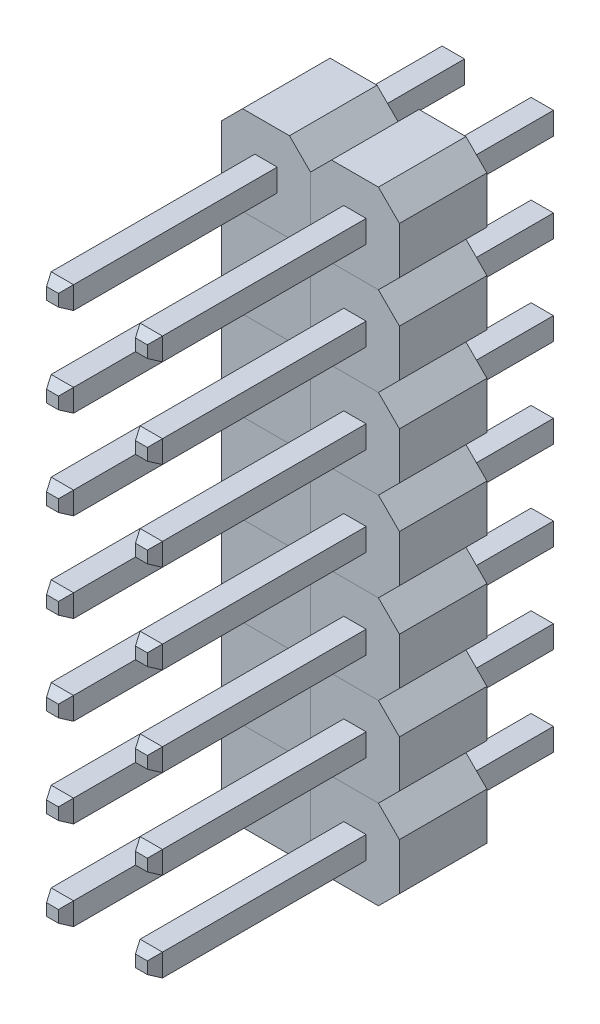
SolidWorks part; units mm, degrees
ref_plane "Спереди" through (0, 0, 0) normal (0, 0, 1) x (1, 0, 0)
ref_plane "Сверху" through (0, 0, 0) normal (0, 1, 0) x (1, 0, 0)
ref_plane "Справа" through (0, 0, 0) normal (1, 0, 0) x (0, 0, -1)
sketch "Эскиз1" plane through (0, 0, 0) normal (0, 0, 1) x (1, 0, 0)
  line L1 (-2.54, -8.89) -> (0, -8.89)
  line L2 (-2.54, -8.89) -> (-2.54, -6.35)
  line L3 (-2.54, -6.35) -> (0, -6.35)
  line L4 (0, -8.89) -> (0, -6.35)
  line L5 (0, -55) -> (0, 55) construction
  line L6 (-2.54, -8.89) -> (0, -6.35) construction
  point P6 (-1.27, -7.62)
  dimension "D1" = 2.54
  dimension "D2" = 7.62
extrude "Бобышка-Вытянуть1" add sketch "Эскиз1" along normal blind 2.5
chamfer "Фаска1" distance 0.6 angle 45 4 edges at (-2.54, -6.35, 1.25) (-2.54, -8.89, 1.25) (0, -8.89, 1.25) (0, -6.35, 1.25)
sketch "Эскиз2" plane through (0, 0, 0) normal (0, 0, -1) x (-1, 0, 0)
  line L0 (1.59, -7.94) -> (0.95, -7.3) construction
  line L1 (1.59, -7.94) -> (0.95, -7.94)
  line L2 (1.59, -7.94) -> (1.59, -7.3)
  line L3 (1.59, -7.3) -> (0.95, -7.3)
  line L4 (0.95, -7.94) -> (0.95, -7.3)
  line L5 (0.95, -7.94) -> (1.59, -7.3) construction
  line L7 (2.54, -8.89) -> (0, -6.35) construction
  point P8 (1.27, -7.62)
  point P11 (1.27, -7.62)
  dimension "D1" = 0.64
extrude "Бобышка-Вытянуть2" add sketch "Эскиз2" along normal blind 3 and the other way blind 8.6
chamfer "Фаска2" distance 0.15 angle 62 8 edges at (-1.59, -7.62, -3) (-1.27, -7.3, -3) (-0.95, -7.62, -3) (-1.27, -7.94, -3) (-1.27, -7.3, 8.6) (-0.95, -7.62, 8.6) (-1.27, -7.94, 8.6) (-1.59, -7.62, 8.6)
pattern_linear "Линейный массив5" count 2 spacing 2.54 along (1, 0, 0) count 7 spacing 2.54 along (0, 1, 0) of "Бобышка-Вытянуть1", "Бобышка-Вытянуть2", "Фаска2"
equation "\"N\"= 14"
equation "\"D2@Линейный массив3\"=\"N\"/2"
equation "\"D2@Линейный массив5\"=\"N\"/2"
equation "\"D2@Эскиз1\"=((\"N\"/2)-1)/2*2.54"
